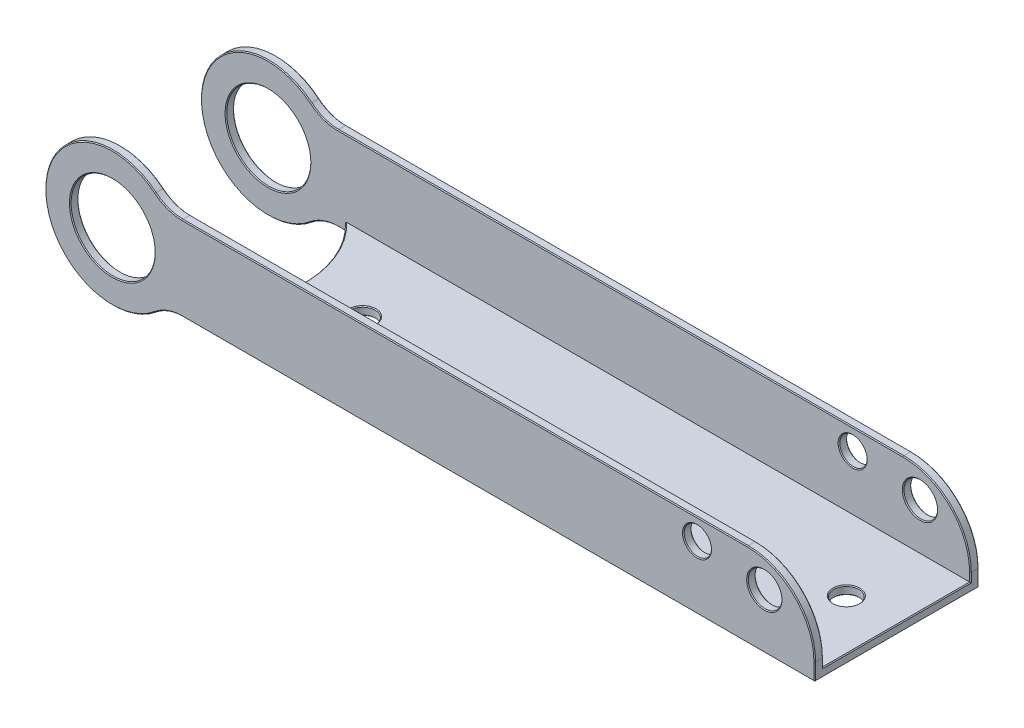
SolidWorks part; units mm, degrees
ref_plane "正面" through (0, 0, 0) normal (0, 0, 1) x (1, 0, 0)
ref_plane "平面" through (0, 0, 0) normal (0, 1, 0) x (1, 0, 0)
ref_plane "右側面" through (0, 0, 0) normal (1, 0, 0) x (0, 0, -1)
sketch "ArmB-L" plane through (0, 0, 0) normal (0, 0, 1) x (1, 0, 0)
  line L0 (12.49, 10) -> (12.49, -10) construction
  line L1 (12.49, 10) -> (167, 10)
  line L3 (12.49, -10) -> (167, -10)
  line L4 (167, 10) -> (167, -10)
  arc A0 (12.49, 10) -> (12.49, -10) centre (0, 0) ccw
  dimension "D1" = 32
  dimension "D2" = 167
  dimension "D3" = 10
extrude "ArmB-W" add sketch "ArmB-L" along normal mid plane 39
fillet "ﾌｨﾚｯﾄ1" radius 16 1 edges at (167, 10, 0)
fillet "ﾌｨﾚｯﾄ2" radius 10 2 edges at (12.49, -10, 0) (12.49, 10, 0)
sketch "ｽｹｯﾁ2" plane through (0, 0, 0) normal (0, 0, 1) x (1, 0, 0)
  circle A0 centre (0, 0) radius 10
  dimension "D1" = 20
extrude "ｶｯﾄ - 押し出し1" cut sketch "ｽｹｯﾁ2" against normal through all both and the other way through all
sketch "ｽｹｯﾁ3" plane through (0, 0, 0) normal (0, 1, 0) x (1, 0, 0)
  line L0 (-16, 19.5) -> (-16, -19.5) construction
  line L1 (-16, 17.5) -> (18.4241, 17.5)
  line L2 (-16, 17.5) -> (-16, -17.5)
  line L3 (-16, -17.5) -> (18.4241, -17.5)
  line L5 (-16, -19.5) -> (10.2235, -19.5) construction
  line L7 (10.2235, 19.5) -> (-16, 19.5) construction
  arc A0 (18.4241, 17.5) -> (18.4241, -17.5) centre (2, 0) cw
  dimension "D1" = 24
  dimension "D2" = 2
  dimension "D3" = 2
  dimension "D4" = 18
extrude "ｶｯﾄ - 押し出し2" cut sketch "ｽｹｯﾁ3" against normal through all both and the other way through all
sketch "ArmB-t" plane through (0, 0, 0) normal (1, 0, 0) x (0, 0, -1)
  line L0 (-19.5, 10) -> (19.5, 10) construction
  line L1 (-17.5, -8) -> (17.5, -8)
  line L2 (-17.5, -8) -> (-17.5, 10)
  line L3 (-17.5, 10) -> (17.5, 10)
  line L4 (17.5, -8) -> (17.5, 10)
  line L7 (17.5, 16) -> (17.5, -16) construction
  line L8 (-17.5, -16) -> (-17.5, 16) construction
  line L9 (-19.5, -10) -> (19.5, -10) construction
  dimension "D1" = 2
extrude "ｶｯﾄ - 押し出し3" cut sketch "ArmB-t" along normal through all
sketch "ｽｹｯﾁ5" plane through (0, 0, 19.5) normal (0, 0, 1) x (1, 0, 0)
  line L0 (167, -10) -> (167, -6) construction
  line L1 (16.6132, -10) -> (167, -10) construction
  circle A0 centre (155, 3) radius 4
  circle A1 centre (139, 5) radius 3.25
  dimension "D1" = 12
  dimension "D2" = 28
  dimension "D4" = 15
  dimension "D5" = 8
  dimension "D6" = 6.5
  dimension "D3" = 13
extrude "ｶｯﾄ - 押し出し4" cut sketch "ｽｹｯﾁ5" against normal through all
sketch "ｽｹｯﾁ6" plane through (0, -10, 0) normal (0, -1, 0) x (1, 0, 0)
  line L0 (167, 19.5) -> (167, -19.5) construction
  circle A0 centre (155, 0) radius 3
  circle A1 centre (40, 0) radius 3
  dimension "D1" = 12
  dimension "D3" = 6
  dimension "D4" = 6
  dimension "D2" = 127
extrude "ｶｯﾄ - 押し出し5" cut sketch "ｽｹｯﾁ6" against normal through all
chamfer "面取り1" distance 0.2 angle 45 48 edges at (142.25, 5, 19.5) (142.25, 5, 17.5) (159, 3, 19.5) (159, 3, 17.5) (135.75, 5, -17.5) (142.25, 5, -19.5) (151, 3, -17.5) (159, 3, -19.5) (10, 0, 19.5) (10, 0, 17.5) (-10, 0, -17.5) (10, 0, -19.5) (17.5187, -10, -17.5) (13.2164, -10.5946, -17.5) (-16, 0, -17.5) (13.2164, 10.5946, -17.5) (83.8066, 10, -17.5) (167, -7, -17.5) (162.3137, 5.3137, -17.5) (17.5187, -10, 17.5) (13.2164, -10.5946, 17.5) (-16, 0, 17.5) (13.2164, 10.5946, 17.5) (167, -7, 17.5) (83.8066, 10, 17.5) (162.3137, 5.3137, 17.5) (167, -8, 0) (167, -8, 19.5) (167, -8, -19.5) (162.3137, 5.3137, 19.5) (162.3137, 5.3137, -19.5) (83.8066, 10, 19.5) (83.8066, 10, -19.5) (13.2164, 10.5946, 19.5) (13.2164, 10.5946, -19.5) (-16, 0, 19.5) (-16, 0, -19.5) (13.2164, -10.5946, 19.5) (13.2164, -10.5946, -19.5) (91.8066, -10, 19.5) (167, -10, 0) (91.8066, -10, -19.5) (155, -10, -3) (155, -8, 3) (40, -10, -3) (40, -8, 3) (26, -10, 0) (26, -8, 0)
